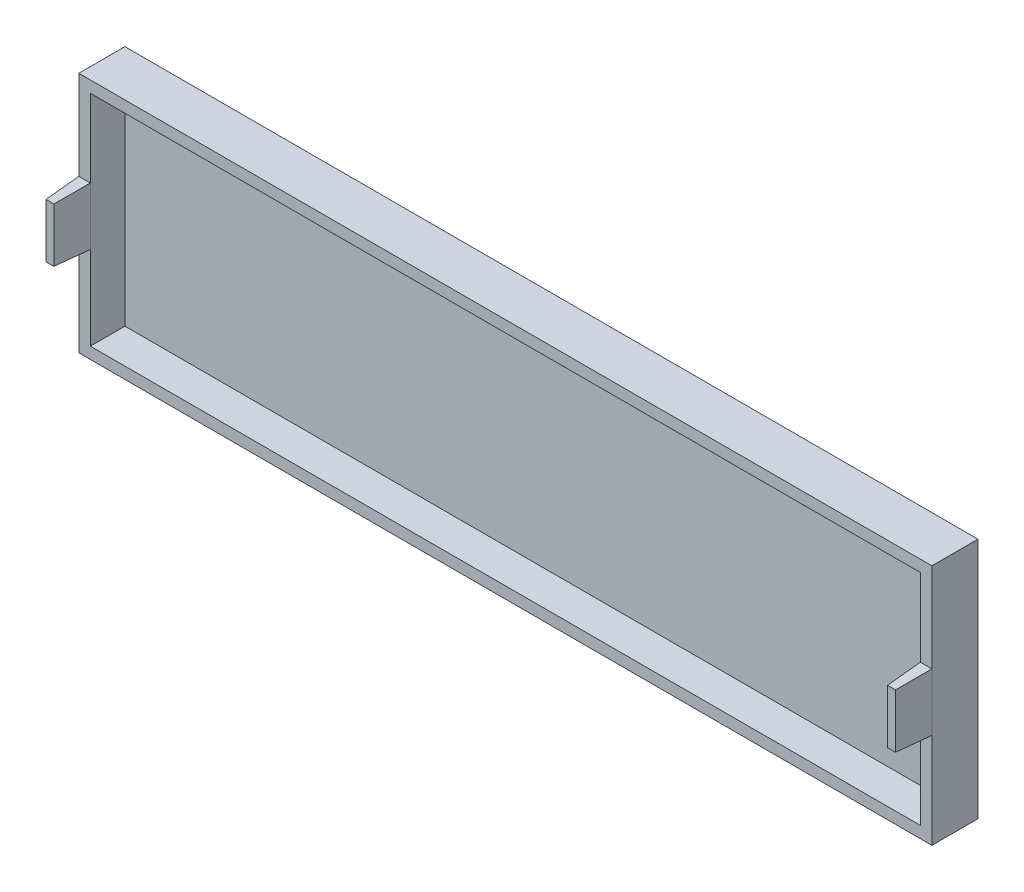
SolidWorks part; units mm, degrees
ref_plane "Piano frontale" through (0, 0, 0) normal (0, 0, 1) x (1, 0, 0)
ref_plane "Piano superiore" through (0, 0, 0) normal (0, 1, 0) x (1, 0, 0)
ref_plane "Piano destro" through (0, 0, 0) normal (1, 0, 0) x (0, 0, -1)
sketch "Schizzo1" plane through (0, 0, 0) normal (0, 0, 1) x (1, 0, 0)
  line L1 (74, -21) -> (-74, -21)
  line L2 (74, -21) -> (74, 21)
  line L3 (74, 21) -> (-74, 21)
  line L4 (-74, -21) -> (-74, 21)
  line L5 (74, -21) -> (-74, 21) construction
  line L6 (74, 21) -> (-74, -21) construction
  point P0 (0, 0)
  dimension "D1" = 148
  dimension "D2" = 42
extrude "Estrusione-Estrusione1" add sketch "Schizzo1" along normal blind 2
sketch "Schizzo2" plane through (0, 0, 2) normal (0, 0, 1) x (1, 0, 0)
  line L0 (72, 19) -> (-72, 19)
  line L1 (-72, 19) -> (-72, -19)
  line L2 (-72, -19) -> (72, -19)
  line L3 (72, -19) -> (72, 19)
  line L4 (-74, 21) -> (-74, -21)
  line L5 (-74, -21) -> (74, -21)
  line L6 (74, -21) -> (74, 21)
  line L7 (74, 21) -> (-74, 21)
  line L8 (-74, 21) -> (-74, -21)
  line L9 (-74, -21) -> (74, -21)
  line L10 (74, -21) -> (74, 21)
  line L11 (74, 21) -> (-74, 21)
  dimension "D1" = 0
  dimension "D2" = 2
extrude "Estrusione-Estrusione2" add sketch "Schizzo2" along normal blind 6
sketch "Schizzo3" plane through (0, 0, 8) normal (0, 0, 1) x (1, 0, 0)
  line L0 (-74, -4.4846) -> (-74, 5.5154)
  line L1 (-74, 21) -> (-74, -21) construction
  line L2 (-74, 5.5154) -> (-72, 5.5154)
  line L3 (-72, 19) -> (-72, -19) construction
  line L4 (-72, 5.5154) -> (-72, -4.4846)
  line L5 (-72, -4.4846) -> (-74, -4.4846)
  point P5 (-74, 0.5154)
  dimension "D1" = 10
extrude "Estrusione-Estrusione3" add sketch "Schizzo3" along normal blind 6 draft 3
mirror "Specchia1" about plane through (0, 0, 0) normal (1, 0, 0) of "Estrusione-Estrusione3"
